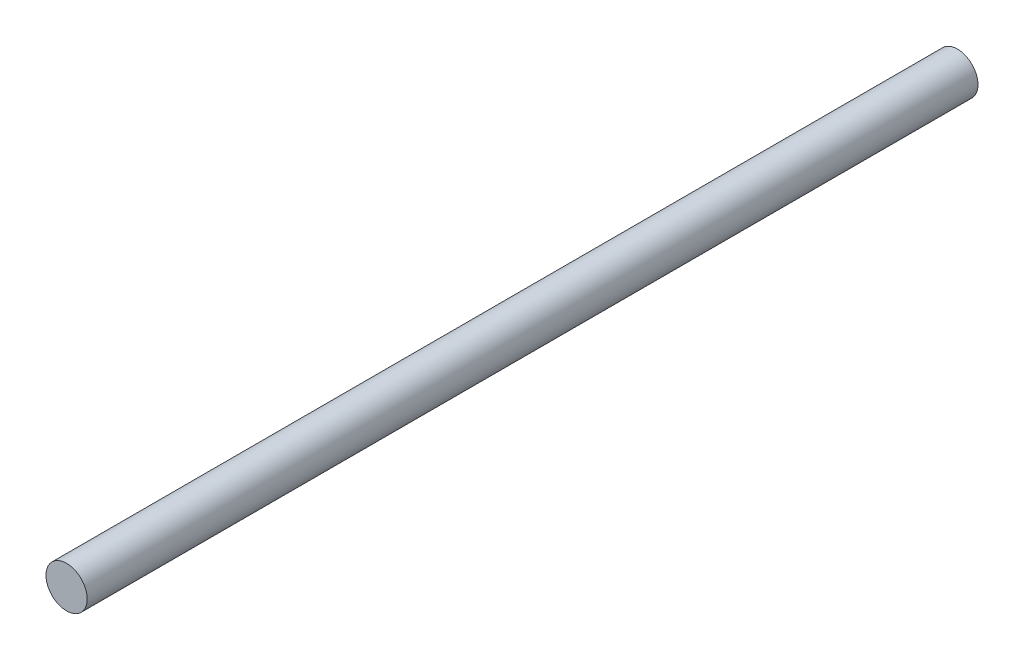
SolidWorks part; units mm, degrees
material "Cast Carbon Steel"
ref_plane "Front Plane" through (0, 0, 0) normal (0, 0, 1) x (1, 0, 0)
ref_plane "Top Plane" through (0, 0, 0) normal (0, 1, 0) x (1, 0, 0)
ref_plane "Right Plane" through (0, 0, 0) normal (1, 0, 0) x (0, 0, -1)
sketch "Sketch1" plane through (0, 0, 0) normal (0, 0, 1) x (1, 0, 0)
  circle A0 centre (0, 0) radius 4.7625
  dimension "D1" = 9.525
extrude "Boss-Extrude1" add sketch "Sketch1" along normal blind 205.74 contours A0
